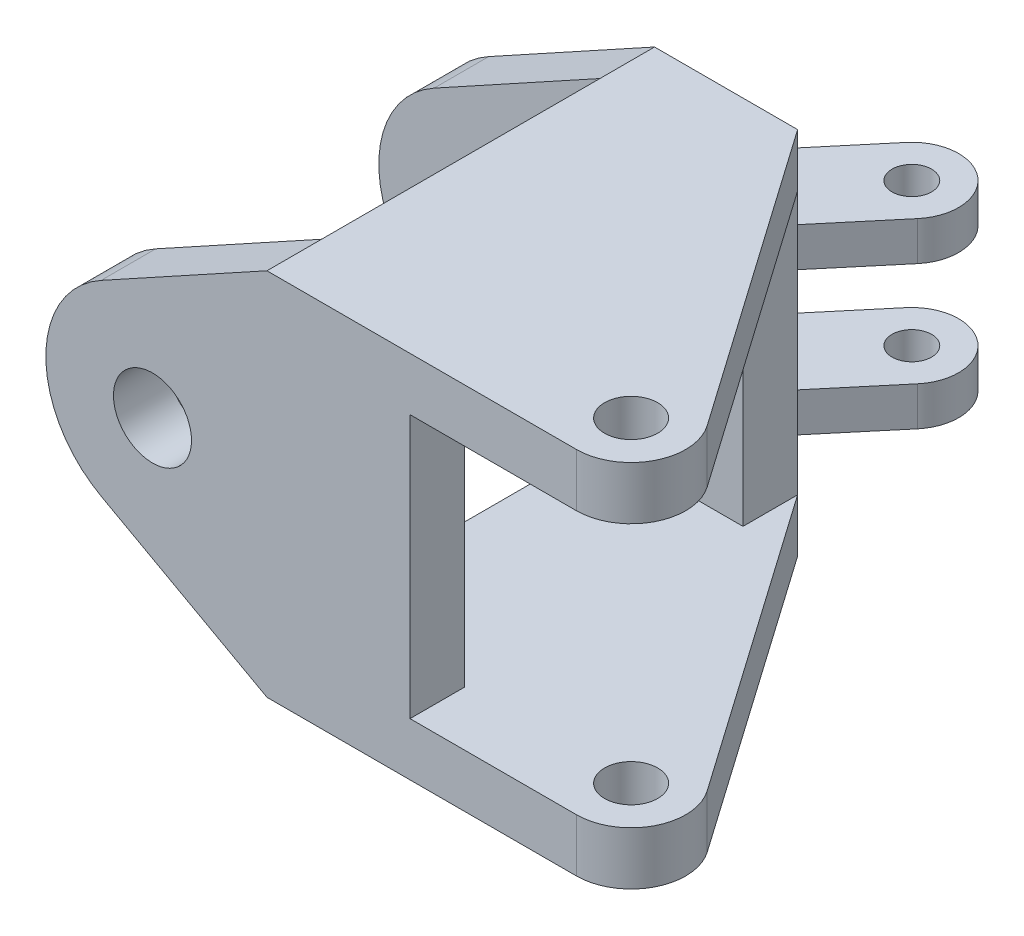
SolidWorks part; units mm, degrees
ref_plane "Front Plane" through (0, 0, 0) normal (0, 0, 1) x (1, 0, 0)
ref_plane "Top Plane" through (0, 0, 0) normal (0, 1, 0) x (1, 0, 0)
ref_plane "Right Plane" through (0, 0, 0) normal (1, 0, 0) x (0, 0, -1)
sketch "Sketch1" plane through (0, 0, 0) normal (0, 0, 1) x (1, 0, 0)
  line L0 (0, 0) -> (495, 0) construction
  line L1 (495, -355) -> (495, 355)
  line L2 (495, 355) -> (220, 355)
  line L3 (220, 355) -> (-98.8104, 179.6149)
  line L4 (495, -355) -> (220, -355)
  line L5 (220, -355) -> (-98.8104, -179.6149)
  arc A0 (-98.8104, 179.6149) -> (-98.8104, -179.6149) centre (0, 0) ccw
  circle A1 centre (0, 0) radius 75
  dimension "D1" = 410
  dimension "D2" = 150
  dimension "D3" = 495
  dimension "D4" = 275
  dimension "D5" = 710
extrude "Boss-Extrude1" add sketch "Sketch1" against normal blind 105
sketch "Sketch3" plane through (0, 355, 0) normal (0, 1, 0) x (1, 0, 0)
  line L0 (220, 105) -> (220, 745)
  line L1 (220, 745) -> (495, 745)
  line L2 (495, 745) -> (900.9903, 165.1858)
  line L3 (815, 0) -> (495, 0)
  arc A0 (900.9903, 165.1858) -> (815, 0) centre (815, 104.9747) cw
  circle A1 centre (815, 104.9747) radius 51
  line M6 (495, 0) -> (495, 105)
  line M7 (495, 105) -> (220, 105)
  dimension "D3" = 55
  dimension "D5" = 102
  dimension "D6" = 104.9747
  dimension "D1" = 640
  dimension "D2" = 275
  dimension "D4" = 595
extrude "Boss-Extrude3" add sketch "Sketch3" against normal blind 102 contours A0 L2 L1 L0 L3 A1 M7 M6
mirror "Mirror1" about plane through (0, 0, 0) normal (0, 1, 0) of "Boss-Extrude1", "Boss-Extrude3"
sketch "Sketch7" plane through (0, 0, -745) normal (0, 0, -1) x (-1, 0, 0)
  line L4 (-495, -355) -> (-220, -355)
  line L5 (-220, -355) -> (-220, -253)
  line L6 (-220, -253) -> (-495, -253)
  line L7 (-495, -253) -> (-495, -355)
  line L8 (-495, -355) -> (-220, -355)
  line L9 (-220, -355) -> (-220, -253)
  line L10 (-220, -253) -> (-495, -253)
  line L11 (-495, -253) -> (-495, -355)
  line L13 (-495, 355) -> (-495, -355)
  line L14 (-220, 355) -> (-495, 355)
  line L15 (98.8104, 179.6149) -> (-220, 355)
  line L16 (-220, -355) -> (98.8104, -179.6149)
  line L17 (-495, -355) -> (-220, -355)
  line L18 (-495, 355) -> (-495, -355)
  line L19 (-220, 355) -> (-495, 355)
  line L20 (98.8104, 179.6149) -> (-220, 355)
  line L21 (-220, -355) -> (98.8104, -179.6149)
  line L22 (-495, -355) -> (-220, -355)
  circle A1 centre (0, 0) radius 75
  circle A2 centre (0, 0) radius 75
  arc A3 (98.8104, -179.6149) -> (98.8104, 179.6149) centre (0, 0) ccw
  arc A4 (98.8104, -179.6149) -> (98.8104, 179.6149) centre (0, 0) ccw
  line M13 (-220, -355) -> (-220, -253)
  line M14 (-220, -253) -> (-495, -253)
  dimension "D1" = 0
  dimension "D2" = 0
  dimension "D3" = 0
extrude "Boss-Extrude4" add sketch "Sketch7" against normal blind 105 contours L21 A4 L20 L19 L18 A2 M14 M13
sketch "Sketch8" plane through (0, 355, 0) normal (0, 1, 0) x (1, 0, 0)
  line L0 (220, 745) -> (440.5581, 1007.8509)
  line L1 (578.4461, 892.1491) -> (454.9733, 745)
  line L2 (220, 745) -> (495, 745) construction
  arc A0 (440.5581, 1007.8509) -> (578.4461, 892.1491) centre (509.5021, 950) cw
  circle A1 centre (509.5021, 950) radius 38
  line M4 (495, 745) -> (220, 745)
  dimension "D2" = 76
  dimension "D3" = 90
  dimension "D1" = 205
  dimension "D4" = 50
extrude "Boss-Extrude5" add sketch "Sketch8" against normal blind 75 from offset 180 contours A0 L0 L1 A1 M4 offset against normal yes
mirror "Mirror2" about plane through (0, 0, 0) normal (0, 1, 0) of "Boss-Extrude5"
